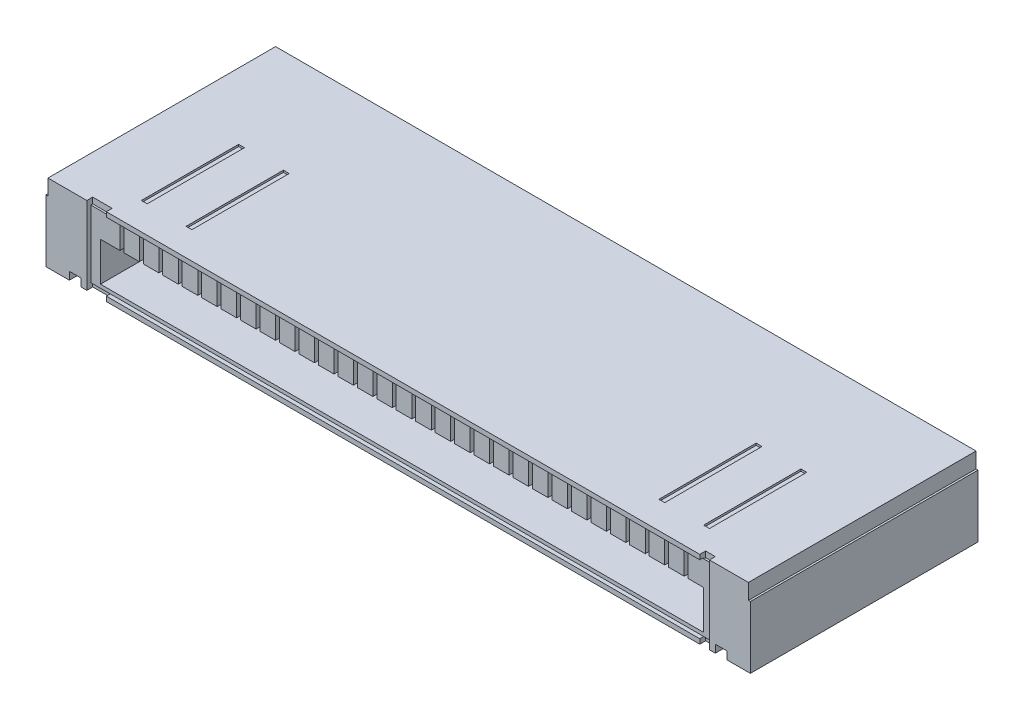
SolidWorks part; units mm, degrees
ref_plane "Plan de face" through (0, 0, 0) normal (0, 0, 1) x (1, 0, 0)
ref_plane "Plan de dessus" through (0, 0, 0) normal (0, 1, 0) x (1, 0, 0)
ref_plane "Plan de droite" through (0, 0, 0) normal (1, 0, 0) x (0, 0, -1)
sketch "Esquisse1" plane through (0, 0, 0) normal (0, 0, 1) x (1, 0, 0)
  line L0 (-42.1545, 0) -> (-21.1545, 0) construction
  line L1 (-42.1545, 2.5) -> (-21.1545, 2.5)
  line L2 (-42.1545, -2.5) -> (-21.1545, -2.5)
  arc A0 (-42.1545, 2.5) -> (-42.1545, -2.5) centre (-42.1545, 0) ccw
  arc A1 (-21.1545, -2.5) -> (-21.1545, 2.5) centre (-21.1545, 0) ccw
  point P3 (-31.6545, 0)
  dimension "D1" = 5
  dimension "D2" = 26
extrude "Boss.-Extru.1" add sketch "Esquisse1" along normal blind 9
sketch "Esquisse3" plane through (0, 0, 9) normal (0, 0, 1) x (1, 0, 0)
  line L0 (-42.1415, 0) -> (-21.1415, 0) construction
  line L1 (-42.1415, 2) -> (-21.1415, 2)
  line L2 (-42.1415, -2) -> (-21.1415, -2)
  arc A0 (-42.1415, 2) -> (-42.1415, -2) centre (-42.1415, 0) ccw
  arc A1 (-21.1415, -2) -> (-21.1415, 2) centre (-21.1415, 0) ccw
  point P3 (-31.6415, 0)
  dimension "D1" = 4
  dimension "D2" = 25
extrude "Enlèv. mat.-Extru.1" cut sketch "Esquisse3" against normal blind 0.15
sketch "Esquisse4" plane through (0, 0, 8.85) normal (0, 0, 1) x (1, 0, 0)
  line L0 (-41.6545, 0.5) -> (-40.6545, 0.5)
  line L1 (-40.6545, 1) -> (-22.6545, 1)
  line L2 (-41.6545, 0.5) -> (-41.6545, -1)
  line L3 (-41.6545, -1) -> (-21.6545, -1)
  line L4 (-21.6545, 0.5) -> (-21.6545, -1)
  line L7 (-40.6545, 0.5) -> (-40.6545, 1)
  line L8 (-22.6545, 1) -> (-22.6545, 0.5)
  line L9 (-22.6545, 0.5) -> (-21.6545, 0.5)
  line L10 (-42.1415, -2) -> (-21.1415, -2) construction
  line L11 (-21.1415, 2) -> (-42.1415, 2) construction
  arc A0 (-42.1545, 2.5) -> (-42.1545, -2.5) centre (-42.1545, 0) ccw construction
  arc A1 (-21.1545, -2.5) -> (-21.1545, 2.5) centre (-21.1545, 0) ccw construction
  point P0 (-31.6545, 0)
  point P11 (-44.6545, 0)
  point P15 (-18.6545, 0)
  dimension "D1" = 3
  dimension "D2" = 3
  dimension "D3" = 1
  dimension "D4" = 1
  dimension "D5" = 1
  dimension "D6" = 0.5
  dimension "D7" = 0.5
  dimension "D8" = 1
extrude "Boss.-Extru.2" add sketch "Esquisse4" along normal blind 6
fillet "Congé1" radius 0.3 1 edges at (-40.6545, 0.5, 11.85)
fillet "Congé2" radius 0.3 1 edges at (-22.6545, 0.5, 11.85)
sketch "Esquisse5" plane through (0, 1, 0) normal (0, 1, 0) x (1, 0, 0)
  line L1 (-22.6545, -8.85) -> (-40.6545, -8.85) construction
  line L2 (-22.6545, -14.85) -> (-40.6545, -14.85) construction
  line L14 (-37.6545, -11.65) -> (-25.6545, -11.65) construction
  line L27 (-31.6545, -8.85) -> (-31.6545, -14.85) construction
  line L28 (-25.5045, -11.65) -> (-25.6545, -11.65)
  line L29 (-25.6545, -11.65) -> (-25.6545, -14.15)
  line L30 (-38.9545, -11.65) -> (-38.8045, -11.65)
  line L31 (-38.9545, -11.65) -> (-38.9545, -14.15)
  line L32 (-38.9545, -14.15) -> (-38.8045, -14.15)
  line L33 (-38.8045, -11.65) -> (-38.8045, -14.15)
  line L34 (-37.8045, -11.65) -> (-37.6545, -11.65)
  line L35 (-37.8045, -11.65) -> (-37.8045, -14.15)
  line L36 (-37.8045, -14.15) -> (-37.6545, -14.15)
  line L37 (-37.6545, -11.65) -> (-37.6545, -14.15)
  line L38 (-25.5045, -14.15) -> (-25.6545, -14.15)
  line L39 (-25.5045, -11.65) -> (-25.5045, -14.15)
  line L40 (-24.3545, -14.15) -> (-24.5045, -14.15)
  line L41 (-24.5045, -11.65) -> (-24.5045, -14.15)
  line L42 (-24.3545, -11.65) -> (-24.3545, -14.15)
  line L43 (-24.3545, -11.65) -> (-24.5045, -11.65)
  point P42 (-31.6545, -11.65)
  dimension "D1" = 0.15
  dimension "D2" = 0.15
  dimension "D3" = 2.5
  dimension "D4" = 1
  dimension "D5" = 1
  dimension "D6" = 12
  dimension "D7" = 2.5
  dimension "D8" = 0.7
extrude "Enlèv. mat.-Extru.2" cut sketch "Esquisse5" against normal blind 0.05
sketch "Esquisse6" plane through (0, 0, 14.85) normal (0, 0, 1) x (1, 0, 0)
  line L1 (-39.6545, 0.8785) -> (-23.6545, 0.8785)
  line L2 (-39.6545, 0.8785) -> (-39.6545, -0.8785)
  line L3 (-39.6545, -0.8785) -> (-23.6545, -0.8785)
  line L4 (-23.6545, 0.8785) -> (-23.6545, -0.8785)
  line L5 (-39.6545, 0.8785) -> (-23.6545, -0.8785) construction
  line L6 (-39.6545, -0.8785) -> (-23.6545, 0.8785) construction
  line L8 (-22.6545, 0.8) -> (-22.6545, 1) construction
  line L9 (-40.6545, 1) -> (-40.6545, 0.8) construction
  point P0 (-31.6545, 0)
  dimension "D1" = 1
  dimension "D2" = 1
extrude "Enlèv. mat.-Extru.3" cut sketch "Esquisse6" against normal blind 0.1
sketch "Esquisse7" plane through (0, 0, 14.75) normal (0, 0, 1) x (1, 0, 0)
  line L0 (-39.6545, 0.8785) -> (-39.6545, -0.8785) construction
  line L1 (-39.4045, 0.2124) -> (-23.9045, 0.2124)
  line L2 (-39.4045, 0.2124) -> (-39.4045, -0.7876)
  line L3 (-39.4045, -0.7876) -> (-23.9045, -0.7876)
  line L4 (-23.9045, 0.2124) -> (-23.9045, -0.7876)
  line L5 (-39.4045, 0.2124) -> (-23.9045, -0.7876) construction
  line L6 (-39.4045, -0.7876) -> (-23.9045, 0.2124) construction
  line L7 (-23.6545, -0.8785) -> (-23.6545, 0.8785) construction
  point P0 (-31.6545, -0.2876)
  dimension "D1" = 0.25
  dimension "D2" = 0.25
  dimension "D3" = 1
extrude "Enlèv. mat.-Extru.4" cut sketch "Esquisse7" against normal blind 4
sketch "Esquisse9" plane through (0, 0, 14.75) normal (0, 0, 1) x (1, 0, 0)
  line L0 (-23.6545, 0.8785) -> (-39.6545, 0.8785) construction
  line L1 (-38.9045, 0.8785) -> (-38.8045, 0.8785)
  line L2 (-38.9045, 0.8785) -> (-38.9045, 0.2124)
  line L3 (-38.9045, 0.2124) -> (-38.8045, 0.2124)
  line L4 (-38.8045, 0.8785) -> (-38.8045, 0.2124)
  line L5 (-23.9045, 0.2124) -> (-39.4045, 0.2124) construction
  line L6 (-39.4045, 0.2124) -> (-39.4045, -0.7876) construction
  line L7 (-38.4045, 0.8785) -> (-38.4045, 0.2124)
  line L8 (-38.4045, 0.8785) -> (-38.3045, 0.8785)
  line L9 (-38.3045, 0.8785) -> (-38.3045, 0.2124)
  line L10 (-38.4045, 0.2124) -> (-38.3045, 0.2124)
  line L11 (-37.9045, 0.8785) -> (-37.9045, 0.2124)
  line L12 (-37.9045, 0.8785) -> (-37.8045, 0.8785)
  line L13 (-37.8045, 0.8785) -> (-37.8045, 0.2124)
  line L14 (-37.9045, 0.2124) -> (-37.8045, 0.2124)
  line L15 (-37.4045, 0.8785) -> (-37.4045, 0.2124)
  line L16 (-37.4045, 0.8785) -> (-37.3045, 0.8785)
  line L17 (-37.3045, 0.8785) -> (-37.3045, 0.2124)
  line L18 (-37.4045, 0.2124) -> (-37.3045, 0.2124)
  line L19 (-36.9045, 0.8785) -> (-36.9045, 0.2124)
  line L20 (-36.9045, 0.8785) -> (-36.8045, 0.8785)
  line L21 (-36.8045, 0.8785) -> (-36.8045, 0.2124)
  line L22 (-36.9045, 0.2124) -> (-36.8045, 0.2124)
  line L23 (-36.4045, 0.8785) -> (-36.4045, 0.2124)
  line L24 (-36.4045, 0.8785) -> (-36.3045, 0.8785)
  line L25 (-36.3045, 0.8785) -> (-36.3045, 0.2124)
  line L26 (-36.4045, 0.2124) -> (-36.3045, 0.2124)
  line L27 (-35.9045, 0.8785) -> (-35.9045, 0.2124)
  line L28 (-35.9045, 0.8785) -> (-35.8045, 0.8785)
  line L29 (-35.8045, 0.8785) -> (-35.8045, 0.2124)
  line L30 (-35.9045, 0.2124) -> (-35.8045, 0.2124)
  line L31 (-35.4045, 0.8785) -> (-35.4045, 0.2124)
  line L32 (-35.4045, 0.8785) -> (-35.3045, 0.8785)
  line L33 (-35.3045, 0.8785) -> (-35.3045, 0.2124)
  line L34 (-35.4045, 0.2124) -> (-35.3045, 0.2124)
  line L35 (-34.9045, 0.8785) -> (-34.9045, 0.2124)
  line L36 (-34.9045, 0.8785) -> (-34.8045, 0.8785)
  line L37 (-34.8045, 0.8785) -> (-34.8045, 0.2124)
  line L38 (-34.9045, 0.2124) -> (-34.8045, 0.2124)
  line L39 (-34.4045, 0.8785) -> (-34.4045, 0.2124)
  line L40 (-34.4045, 0.8785) -> (-34.3045, 0.8785)
  line L41 (-34.3045, 0.8785) -> (-34.3045, 0.2124)
  line L42 (-34.4045, 0.2124) -> (-34.3045, 0.2124)
  line L43 (-33.9045, 0.8785) -> (-33.9045, 0.2124)
  line L44 (-33.9045, 0.8785) -> (-33.8045, 0.8785)
  line L45 (-33.8045, 0.8785) -> (-33.8045, 0.2124)
  line L46 (-33.9045, 0.2124) -> (-33.8045, 0.2124)
  line L47 (-33.4045, 0.8785) -> (-33.4045, 0.2124)
  line L48 (-33.4045, 0.8785) -> (-33.3045, 0.8785)
  line L49 (-33.3045, 0.8785) -> (-33.3045, 0.2124)
  line L50 (-33.4045, 0.2124) -> (-33.3045, 0.2124)
  line L51 (-32.9045, 0.8785) -> (-32.9045, 0.2124)
  line L52 (-32.9045, 0.8785) -> (-32.8045, 0.8785)
  line L53 (-32.8045, 0.8785) -> (-32.8045, 0.2124)
  line L54 (-32.9045, 0.2124) -> (-32.8045, 0.2124)
  line L55 (-32.4045, 0.8785) -> (-32.4045, 0.2124)
  line L56 (-32.4045, 0.8785) -> (-32.3045, 0.8785)
  line L57 (-32.3045, 0.8785) -> (-32.3045, 0.2124)
  line L58 (-32.4045, 0.2124) -> (-32.3045, 0.2124)
  line L59 (-31.9045, 0.8785) -> (-31.9045, 0.2124)
  line L60 (-31.9045, 0.8785) -> (-31.8045, 0.8785)
  line L61 (-31.8045, 0.8785) -> (-31.8045, 0.2124)
  line L62 (-31.9045, 0.2124) -> (-31.8045, 0.2124)
  line L63 (-31.4045, 0.8785) -> (-31.4045, 0.2124)
  line L64 (-31.4045, 0.8785) -> (-31.3045, 0.8785)
  line L65 (-31.3045, 0.8785) -> (-31.3045, 0.2124)
  line L66 (-31.4045, 0.2124) -> (-31.3045, 0.2124)
  line L67 (-30.9045, 0.8785) -> (-30.9045, 0.2124)
  line L68 (-30.9045, 0.8785) -> (-30.8045, 0.8785)
  line L69 (-30.8045, 0.8785) -> (-30.8045, 0.2124)
  line L70 (-30.9045, 0.2124) -> (-30.8045, 0.2124)
  line L71 (-30.4045, 0.8785) -> (-30.4045, 0.2124)
  line L72 (-30.4045, 0.8785) -> (-30.3045, 0.8785)
  line L73 (-30.3045, 0.8785) -> (-30.3045, 0.2124)
  line L74 (-30.4045, 0.2124) -> (-30.3045, 0.2124)
  line L75 (-29.9045, 0.8785) -> (-29.9045, 0.2124)
  line L76 (-29.9045, 0.8785) -> (-29.8045, 0.8785)
  line L77 (-29.8045, 0.8785) -> (-29.8045, 0.2124)
  line L78 (-29.9045, 0.2124) -> (-29.8045, 0.2124)
  line L79 (-29.4045, 0.8785) -> (-29.4045, 0.2124)
  line L80 (-29.4045, 0.8785) -> (-29.3045, 0.8785)
  line L81 (-29.3045, 0.8785) -> (-29.3045, 0.2124)
  line L82 (-29.4045, 0.2124) -> (-29.3045, 0.2124)
  line L83 (-28.9045, 0.8785) -> (-28.9045, 0.2124)
  line L84 (-28.9045, 0.8785) -> (-28.8045, 0.8785)
  line L85 (-28.8045, 0.8785) -> (-28.8045, 0.2124)
  line L86 (-28.9045, 0.2124) -> (-28.8045, 0.2124)
  line L87 (-28.4045, 0.8785) -> (-28.4045, 0.2124)
  line L88 (-28.4045, 0.8785) -> (-28.3045, 0.8785)
  line L89 (-28.3045, 0.8785) -> (-28.3045, 0.2124)
  line L90 (-28.4045, 0.2124) -> (-28.3045, 0.2124)
  line L91 (-27.9045, 0.8785) -> (-27.9045, 0.2124)
  line L92 (-27.9045, 0.8785) -> (-27.8045, 0.8785)
  line L93 (-27.8045, 0.8785) -> (-27.8045, 0.2124)
  line L94 (-27.9045, 0.2124) -> (-27.8045, 0.2124)
  line L95 (-27.4045, 0.8785) -> (-27.4045, 0.2124)
  line L96 (-27.4045, 0.8785) -> (-27.3045, 0.8785)
  line L97 (-27.3045, 0.8785) -> (-27.3045, 0.2124)
  line L98 (-27.4045, 0.2124) -> (-27.3045, 0.2124)
  line L99 (-26.9045, 0.8785) -> (-26.9045, 0.2124)
  line L100 (-26.9045, 0.8785) -> (-26.8045, 0.8785)
  line L101 (-26.8045, 0.8785) -> (-26.8045, 0.2124)
  line L102 (-26.9045, 0.2124) -> (-26.8045, 0.2124)
  line L103 (-26.4045, 0.8785) -> (-26.4045, 0.2124)
  line L104 (-26.4045, 0.8785) -> (-26.3045, 0.8785)
  line L105 (-26.3045, 0.8785) -> (-26.3045, 0.2124)
  line L106 (-26.4045, 0.2124) -> (-26.3045, 0.2124)
  line L107 (-25.9045, 0.8785) -> (-25.9045, 0.2124)
  line L108 (-25.9045, 0.8785) -> (-25.8045, 0.8785)
  line L109 (-25.8045, 0.8785) -> (-25.8045, 0.2124)
  line L110 (-25.9045, 0.2124) -> (-25.8045, 0.2124)
  line L111 (-25.4045, 0.8785) -> (-25.4045, 0.2124)
  line L112 (-25.4045, 0.8785) -> (-25.3045, 0.8785)
  line L113 (-25.3045, 0.8785) -> (-25.3045, 0.2124)
  line L114 (-25.4045, 0.2124) -> (-25.3045, 0.2124)
  line L115 (-24.9045, 0.8785) -> (-24.9045, 0.2124)
  line L116 (-24.9045, 0.8785) -> (-24.8045, 0.8785)
  line L117 (-24.8045, 0.8785) -> (-24.8045, 0.2124)
  line L118 (-24.9045, 0.2124) -> (-24.8045, 0.2124)
  line L119 (-24.4045, 0.8785) -> (-24.4045, 0.2124)
  line L120 (-24.4045, 0.8785) -> (-24.3045, 0.8785)
  line L121 (-24.3045, 0.8785) -> (-24.3045, 0.2124)
  line L122 (-24.4045, 0.2124) -> (-24.3045, 0.2124)
  line L123 (-38.9045, 0.8785) -> (-38.4045, 0.8785) construction
  dimension "D1" = 0.5
  dimension "D2" = 0.1
  dimension "D4" = 0.5
  dimension "D3" = 30
extrude "Enlèv. mat.-Extru.5" cut sketch "Esquisse9" against normal blind 0.1
sketch "Esquisse10" plane through (0, 0.2124, 0) normal (0, -1, 0) x (1, 0, 0)
  line L0 (-23.9045, 10.75) -> (-39.4045, 10.75) construction
  line L1 (-38.9045, 14.65) -> (-38.8045, 14.65)
  line L2 (-38.9045, 14.65) -> (-38.9045, 10.75)
  line L3 (-38.9045, 10.75) -> (-38.8045, 10.75)
  line L4 (-38.8045, 14.65) -> (-38.8045, 10.75)
  line L5 (-38.4045, 14.65) -> (-38.3045, 14.65)
  line L6 (-38.4045, 14.65) -> (-38.4045, 10.75)
  line L7 (-38.3045, 14.65) -> (-38.3045, 10.75)
  line L8 (-37.9045, 14.65) -> (-37.8045, 14.65)
  line L9 (-37.9045, 14.65) -> (-37.9045, 10.75)
  line L10 (-37.8045, 14.65) -> (-37.8045, 10.75)
  line L11 (-37.4045, 14.65) -> (-37.3045, 14.65)
  line L12 (-37.4045, 14.65) -> (-37.4045, 10.75)
  line L13 (-37.3045, 14.65) -> (-37.3045, 10.75)
  line L14 (-36.9045, 14.65) -> (-36.8045, 14.65)
  line L15 (-36.9045, 14.65) -> (-36.9045, 10.75)
  line L16 (-36.8045, 14.65) -> (-36.8045, 10.75)
  line L17 (-36.4045, 14.65) -> (-36.3045, 14.65)
  line L18 (-36.4045, 14.65) -> (-36.4045, 10.75)
  line L19 (-36.3045, 14.65) -> (-36.3045, 10.75)
  line L20 (-35.9045, 14.65) -> (-35.8045, 14.65)
  line L21 (-35.9045, 14.65) -> (-35.9045, 10.75)
  line L22 (-35.8045, 14.65) -> (-35.8045, 10.75)
  line L23 (-35.4045, 14.65) -> (-35.3045, 14.65)
  line L24 (-35.4045, 14.65) -> (-35.4045, 10.75)
  line L25 (-35.3045, 14.65) -> (-35.3045, 10.75)
  line L26 (-34.9045, 14.65) -> (-34.8045, 14.65)
  line L27 (-34.9045, 14.65) -> (-34.9045, 10.75)
  line L28 (-34.8045, 14.65) -> (-34.8045, 10.75)
  line L29 (-34.4045, 14.65) -> (-34.3045, 14.65)
  line L30 (-34.4045, 14.65) -> (-34.4045, 10.75)
  line L31 (-34.3045, 14.65) -> (-34.3045, 10.75)
  line L32 (-33.9045, 14.65) -> (-33.8045, 14.65)
  line L33 (-33.9045, 14.65) -> (-33.9045, 10.75)
  line L34 (-33.8045, 14.65) -> (-33.8045, 10.75)
  line L35 (-33.4045, 14.65) -> (-33.3045, 14.65)
  line L36 (-33.4045, 14.65) -> (-33.4045, 10.75)
  line L37 (-33.3045, 14.65) -> (-33.3045, 10.75)
  line L38 (-32.9045, 14.65) -> (-32.8045, 14.65)
  line L39 (-32.9045, 14.65) -> (-32.9045, 10.75)
  line L40 (-32.8045, 14.65) -> (-32.8045, 10.75)
  line L41 (-32.4045, 14.65) -> (-32.3045, 14.65)
  line L42 (-32.4045, 14.65) -> (-32.4045, 10.75)
  line L43 (-32.3045, 14.65) -> (-32.3045, 10.75)
  line L44 (-31.9045, 14.65) -> (-31.8045, 14.65)
  line L45 (-31.9045, 14.65) -> (-31.9045, 10.75)
  line L46 (-31.8045, 14.65) -> (-31.8045, 10.75)
  line L47 (-31.4045, 14.65) -> (-31.3045, 14.65)
  line L48 (-31.4045, 14.65) -> (-31.4045, 10.75)
  line L49 (-31.3045, 14.65) -> (-31.3045, 10.75)
  line L50 (-30.9045, 14.65) -> (-30.8045, 14.65)
  line L51 (-30.9045, 14.65) -> (-30.9045, 10.75)
  line L52 (-30.8045, 14.65) -> (-30.8045, 10.75)
  line L53 (-30.4045, 14.65) -> (-30.3045, 14.65)
  line L54 (-30.4045, 14.65) -> (-30.4045, 10.75)
  line L55 (-30.3045, 14.65) -> (-30.3045, 10.75)
  line L56 (-29.9045, 14.65) -> (-29.8045, 14.65)
  line L57 (-29.9045, 14.65) -> (-29.9045, 10.75)
  line L58 (-29.8045, 14.65) -> (-29.8045, 10.75)
  line L59 (-29.4045, 14.65) -> (-29.3045, 14.65)
  line L60 (-29.4045, 14.65) -> (-29.4045, 10.75)
  line L61 (-29.3045, 14.65) -> (-29.3045, 10.75)
  line L62 (-28.9045, 14.65) -> (-28.8045, 14.65)
  line L63 (-28.9045, 14.65) -> (-28.9045, 10.75)
  line L64 (-28.8045, 14.65) -> (-28.8045, 10.75)
  line L65 (-28.4045, 14.65) -> (-28.3045, 14.65)
  line L66 (-28.4045, 14.65) -> (-28.4045, 10.75)
  line L67 (-28.3045, 14.65) -> (-28.3045, 10.75)
  line L68 (-27.9045, 14.65) -> (-27.8045, 14.65)
  line L69 (-27.9045, 14.65) -> (-27.9045, 10.75)
  line L70 (-27.8045, 14.65) -> (-27.8045, 10.75)
  line L71 (-27.4045, 14.65) -> (-27.3045, 14.65)
  line L72 (-27.4045, 14.65) -> (-27.4045, 10.75)
  line L73 (-27.3045, 14.65) -> (-27.3045, 10.75)
  line L74 (-26.9045, 14.65) -> (-26.8045, 14.65)
  line L75 (-26.9045, 14.65) -> (-26.9045, 10.75)
  line L76 (-26.8045, 14.65) -> (-26.8045, 10.75)
  line L77 (-26.4045, 14.65) -> (-26.3045, 14.65)
  line L78 (-26.4045, 14.65) -> (-26.4045, 10.75)
  line L79 (-26.3045, 14.65) -> (-26.3045, 10.75)
  line L80 (-25.9045, 14.65) -> (-25.8045, 14.65)
  line L81 (-25.9045, 14.65) -> (-25.9045, 10.75)
  line L82 (-25.8045, 14.65) -> (-25.8045, 10.75)
  line L83 (-25.4045, 14.65) -> (-25.3045, 14.65)
  line L84 (-25.4045, 14.65) -> (-25.4045, 10.75)
  line L85 (-25.3045, 14.65) -> (-25.3045, 10.75)
  line L86 (-24.9045, 14.65) -> (-24.8045, 14.65)
  line L87 (-24.9045, 14.65) -> (-24.9045, 10.75)
  line L88 (-24.8045, 14.65) -> (-24.8045, 10.75)
  line L89 (-24.4045, 14.65) -> (-24.3045, 14.65)
  line L90 (-24.4045, 14.65) -> (-24.4045, 10.75)
  line L91 (-24.3045, 14.65) -> (-24.3045, 10.75)
  line L92 (-38.9045, 14.65) -> (-38.4045, 14.65) construction
  line L93 (-38.4045, 10.75) -> (-38.3045, 10.75)
  line L94 (-37.9045, 10.75) -> (-37.8045, 10.75)
  line L95 (-37.4045, 10.75) -> (-37.3045, 10.75)
  line L96 (-36.9045, 10.75) -> (-36.8045, 10.75)
  line L97 (-36.4045, 10.75) -> (-36.3045, 10.75)
  line L98 (-35.9045, 10.75) -> (-35.8045, 10.75)
  line L99 (-35.4045, 10.75) -> (-35.3045, 10.75)
  line L100 (-34.9045, 10.75) -> (-34.8045, 10.75)
  line L101 (-34.4045, 10.75) -> (-34.3045, 10.75)
  line L102 (-33.9045, 10.75) -> (-33.8045, 10.75)
  line L103 (-33.4045, 10.75) -> (-33.3045, 10.75)
  line L104 (-32.9045, 10.75) -> (-32.8045, 10.75)
  line L105 (-32.4045, 10.75) -> (-32.3045, 10.75)
  line L106 (-31.9045, 10.75) -> (-31.8045, 10.75)
  line L107 (-31.4045, 10.75) -> (-31.3045, 10.75)
  line L108 (-30.9045, 10.75) -> (-30.8045, 10.75)
  line L109 (-30.4045, 10.75) -> (-30.3045, 10.75)
  line L110 (-29.9045, 10.75) -> (-29.8045, 10.75)
  line L111 (-29.4045, 10.75) -> (-29.3045, 10.75)
  line L112 (-28.9045, 10.75) -> (-28.8045, 10.75)
  line L113 (-28.4045, 10.75) -> (-28.3045, 10.75)
  line L114 (-27.9045, 10.75) -> (-27.8045, 10.75)
  line L115 (-27.4045, 10.75) -> (-27.3045, 10.75)
  line L116 (-26.9045, 10.75) -> (-26.8045, 10.75)
  line L117 (-26.4045, 10.75) -> (-26.3045, 10.75)
  line L118 (-25.9045, 10.75) -> (-25.8045, 10.75)
  line L119 (-25.4045, 10.75) -> (-25.3045, 10.75)
  line L120 (-24.9045, 10.75) -> (-24.8045, 10.75)
  line L121 (-24.4045, 10.75) -> (-24.3045, 10.75)
  dimension "D2" = 0.5
  dimension "D1" = 30
extrude "Enlèv. mat.-Extru.6" cut sketch "Esquisse10" against normal blind 0.1
sketch "Esquisse11" plane through (-21.6545, 0, 0) normal (1, 0, 0) x (0, 0, -1)
  line L1 (-14.85, 0.25) -> (-8.85, 0.25)
  line L2 (-14.85, 0.25) -> (-14.85, -0.25)
  line L3 (-14.85, -0.25) -> (-8.85, -0.25)
  line L4 (-8.85, 0.25) -> (-8.85, -0.25)
  line L5 (-14.85, 0.25) -> (-8.85, -0.25) construction
  line L6 (-14.85, -0.25) -> (-8.85, 0.25) construction
  line L7 (-14.85, -1) -> (-14.85, 0.5) construction
  line L8 (-8.85, -1) -> (-8.85, 0.5) construction
  point P0 (-11.85, 0)
  dimension "D1" = 0.5
extrude "Boss.-Extru.3" [suppressed] add sketch "Esquisse11" along normal blind 1
sketch "Esquisse13" [suppressed] plane through (0, -0.25, 0) normal (0, -1, 0) x (1, 0, 0)
  line L2 (-20.6545, 14.85) -> (-20.6545, 8.85) construction
  line L3 (-20.6545, 12.8999) -> (-21.6545, 11.9855)
  line L4 (-21.6545, 14.85) -> (-21.6545, 8.85) construction
  line L6 (-21.6545, 11.9855) -> (-21.6545, 8.85)
  line L7 (-21.6545, 8.85) -> (-20.6545, 8.85)
  line L8 (-20.6545, 8.85) -> (-20.6545, 12.8999)
extrude "Enlèv. mat.-Extru.7" [suppressed] cut sketch "Esquisse13" against normal blind 1
sketch "Esquisse14" [suppressed] plane through (0, -0.25, 0) normal (0, -1, 0) x (1, 0, 0)
  line L0 (-20.6545, 12.8999) -> (-21.6545, 14.5107)
  line L1 (-21.6545, 14.85) -> (-21.6545, 11.9855) construction
  line L2 (-21.6545, 14.5107) -> (-21.6545, 14.85)
  line L3 (-21.6545, 14.85) -> (-20.6545, 14.85)
  line L4 (-20.6545, 14.85) -> (-20.6545, 12.8999)
extrude "Enlèv. mat.-Extru.8" [suppressed] cut sketch "Esquisse14" against normal blind 1
sketch "Esquisse15" [suppressed] plane through (-21.6545, 0, 0) normal (1, 0, 0) x (0, 0, -1)
  line L0 (-8.85, -1) -> (-8.85, 0.5) construction
  line L1 (-11.9855, 0.25) -> (-8.85, 0.25)
  line L2 (-11.9855, 0.25) -> (-11.9855, -0.25)
  line L3 (-11.9855, -0.25) -> (-8.85, -0.25)
  line L4 (-8.85, 0.25) -> (-8.85, -0.25)
  line L5 (-14.85, -1) -> (-14.85, 0.5) construction
  line L6 (-14.5107, 0.25) -> (-14.85, 0.25)
  line L7 (-14.5107, 0.25) -> (-14.5107, -0.25)
  line L8 (-14.5107, -0.25) -> (-14.85, -0.25)
  line L9 (-14.85, 0.25) -> (-14.85, -0.25)
extrude "Enlèv. mat.-Extru.9" [suppressed] cut sketch "Esquisse15" against normal blind 0.05
fillet "Congé3" [suppressed] radius 0.05
sketch "Esquisse16" plane through (-41.6545, 0, 0) normal (-1, 0, 0) x (0, 0, 1)
  line L0 (14.85, 0.5) -> (14.85, -1) construction
  line L1 (14.85, 0.2491) -> (8.85, 0.2491)
  line L2 (14.85, 0.2491) -> (14.85, -0.2509)
  line L3 (14.85, -0.2509) -> (8.85, -0.2509)
  line L4 (8.85, 0.2491) -> (8.85, -0.2509)
  line L5 (8.85, 0.5) -> (8.85, -1) construction
  dimension "D1" = 0.5
extrude "Boss.-Extru.4" [suppressed] add sketch "Esquisse16" along normal blind 1
sketch "Esquisse17" [suppressed] plane through (0, 0.2491, 0) normal (0, 1, 0) x (1, 0, 0)
  line L0 (-42.6545, -8.85) -> (-41.6545, -8.85)
  line L1 (-41.6545, -8.85) -> (-41.6545, -11.9856)
  line L2 (-41.6545, -14.85) -> (-41.6545, -8.85) construction
  line L3 (-41.6545, -11.9856) -> (-42.6545, -12.9)
  line L4 (-42.6545, -14.85) -> (-42.6545, -8.85) construction
  line L5 (-42.6545, -12.9) -> (-42.6545, -8.85)
  dimension "D1" = 1.95
  dimension "D2" = 132.44
extrude "Enlèv. mat.-Extru.10" [suppressed] cut sketch "Esquisse17" against normal blind 1
sketch "Esquisse18" [suppressed] plane through (0, 0.2491, 0) normal (0, 1, 0) x (1, 0, 0)
  line L0 (-42.6545, -12.9) -> (-41.6545, -14.511)
  line L1 (-41.6545, -14.85) -> (-41.6545, -11.9856) construction
  line L2 (-42.6545, -12.9) -> (-42.6545, -14.85)
  line L3 (-42.6545, -14.85) -> (-41.6545, -14.85)
  line L4 (-41.6545, -14.85) -> (-41.6545, -14.511)
  dimension "D1" = 0.339
extrude "Enlèv. mat.-Extru.11" [suppressed] cut sketch "Esquisse18" against normal blind 1
sketch "Esquisse19" [suppressed] plane through (-41.6545, 0, 0) normal (-1, 0, 0) x (0, 0, 1)
  line L0 (8.85, 0.5) -> (8.85, -1) construction
  line L1 (11.9856, 0.2491) -> (8.85, 0.2491)
  line L2 (11.9856, 0.2491) -> (11.9856, -0.25)
  line L3 (11.9856, -0.25) -> (8.85, -0.25)
  line L4 (8.85, 0.2491) -> (8.85, -0.25)
  line L5 (14.85, 0.5) -> (14.85, -1) construction
  line L6 (14.511, 0.2491) -> (14.85, 0.2491)
  line L7 (14.511, 0.2491) -> (14.511, -0.25)
  line L8 (14.511, -0.25) -> (14.85, -0.25)
  line L9 (14.85, 0.2491) -> (14.85, -0.25)
extrude "Enlèv. mat.-Extru.12" [suppressed] cut sketch "Esquisse19" against normal blind 0.05
fillet "Congé4" [suppressed] radius 0.05
sketch "Esquisse20" plane through (0, 1, 0) normal (0, 1, 0) x (1, 0, 0)
  line L0 (-22.6545, -14.85) -> (-40.6545, -14.85) construction
  line L1 (-39.6545, -14.85) -> (-39.1545, -14.85)
  line L2 (-39.6545, -14.85) -> (-39.6545, -14.7)
  line L3 (-39.6545, -14.7) -> (-39.1545, -14.7)
  line L4 (-39.1545, -14.85) -> (-39.1545, -14.7)
  line L7 (-23.9045, -14.85) -> (-23.6545, -14.85)
  line L8 (-23.9045, -14.85) -> (-23.9045, -14.7)
  line L9 (-23.9045, -14.7) -> (-23.6545, -14.7)
  line L10 (-23.6545, -14.85) -> (-23.6545, -14.7)
  line L11 (-39.6545, -14.75) -> (-39.6545, -14.85) construction
  line L12 (-23.6545, -14.75) -> (-23.6545, -14.85) construction
  dimension "D1" = 0.15
  dimension "D2" = 0.5
  dimension "D3" = 0.15
  dimension "D4" = 0.25
extrude "Enlèv. mat.-Extru.13" cut sketch "Esquisse20" against normal blind 0.15
sketch "Esquisse21" plane through (0, -1, 0) normal (0, -1, 0) x (1, 0, 0)
  line L1 (-37.6545, 14.15) -> (-25.6545, 14.15) construction
  line L2 (-31.6545, 14.85) -> (-31.6545, 8.85) construction
  line L3 (-25.5045, 14.15) -> (-25.6545, 14.15)
  line L4 (-25.6545, 14.15) -> (-25.6545, 11.65)
  line L5 (-41.6545, 14.85) -> (-21.6545, 14.85) construction
  line L6 (-38.9545, 14.15) -> (-38.8045, 14.15)
  line L7 (-38.9545, 14.15) -> (-38.9545, 11.65)
  line L8 (-38.9545, 11.65) -> (-38.8045, 11.65)
  line L9 (-38.8045, 14.15) -> (-38.8045, 11.65)
  line L10 (-37.8045, 14.15) -> (-37.6545, 14.15)
  line L11 (-37.8045, 14.15) -> (-37.8045, 11.65)
  line L12 (-37.8045, 11.65) -> (-37.6545, 11.65)
  line L13 (-37.6545, 14.15) -> (-37.6545, 11.65)
  line L14 (-41.6545, 8.85) -> (-21.6545, 8.85) construction
  line L15 (-25.5045, 11.65) -> (-25.6545, 11.65)
  line L16 (-25.5045, 14.15) -> (-25.5045, 11.65)
  line L17 (-24.3545, 11.65) -> (-24.5045, 11.65)
  line L18 (-24.5045, 14.15) -> (-24.5045, 11.65)
  line L19 (-24.3545, 14.15) -> (-24.3545, 11.65)
  line L20 (-24.3545, 14.15) -> (-24.5045, 14.15)
  point P23 (-31.6545, 14.15)
  dimension "D2" = 12
  dimension "D3" = 0.7
  dimension "D4" = 1
  dimension "D5" = 2.5
  dimension "D6" = 0.15
  dimension "D7" = 2.5
  dimension "D8" = 0.15
  dimension "D10" = 1
extrude "Enlèv. mat.-Extru.14" cut sketch "Esquisse21" against normal blind 0.05
sketch "Esquisse22" plane through (0, -1, 0) normal (0, -1, 0) x (1, 0, 0)
  line L0 (-41.6545, 14.85) -> (-21.6545, 14.85) construction
  line L1 (-40.1045, 14.85) -> (-39.8045, 14.85)
  line L2 (-40.1045, 14.85) -> (-40.1045, 11.85)
  line L3 (-40.1045, 11.85) -> (-39.8045, 11.85)
  line L4 (-39.8045, 14.85) -> (-39.8045, 11.85)
  line L6 (-23.2045, 14.85) -> (-23.5045, 14.85)
  line L7 (-23.5045, 14.85) -> (-23.5045, 11.85)
  line L8 (-23.2045, 11.85) -> (-23.5045, 11.85)
  line L9 (-23.2045, 14.85) -> (-23.2045, 11.85)
  dimension "D1" = 0.3
  dimension "D2" = 0.4
  dimension "D3" = 0.4
  dimension "D4" = 3
extrude "Enlèv. mat.-Extru.15" cut sketch "Esquisse22" against normal blind 0.2
sketch "Sketch1" plane through (0, 0, 0) normal (0, 0, 1) x (1, 0, 0)
  line L1 (-45.9289, 2.7786) -> (-17.5113, 2.7786)
  line L2 (-45.9289, 2.7786) -> (-45.9289, -3.4334)
  line L3 (-45.9289, -3.4334) -> (-17.5113, -3.4334)
  line L4 (-17.5113, 2.7786) -> (-17.5113, -3.4334)
extrude "Cut-Extrude1" cut sketch "Sketch1" along normal blind 9
sketch "Sketch2" plane through (0, -1, 0) normal (0, -1, 0) x (1, 0, 0)
  line L0 (-39.6545, 14.7) -> (-39.1545, 14.7)
  line L1 (-39.6545, 14.7) -> (-39.6545, 14.85)
  line L2 (-39.6545, 14.85) -> (-39.1545, 14.85)
  line L3 (-39.1545, 14.7) -> (-39.1545, 14.85)
  line L4 (-23.9045, 14.7) -> (-23.6545, 14.7)
  line L5 (-23.9045, 14.7) -> (-23.9045, 14.85)
  line L6 (-23.9045, 14.85) -> (-23.6545, 14.85)
  line L7 (-23.6545, 14.7) -> (-23.6545, 14.85)
  line L8 (-39.8045, 14.85) -> (-23.5045, 14.85) construction
  dimension "D1" = 0.5
  dimension "D2" = 0.15
  dimension "D3" = 0.25
  dimension "D4" = 0.15
extrude "Cut-Extrude2" cut sketch "Sketch2" against normal up to vertex (0.1215 mm away) up to point (-39.6545, -0.8785, 14.85)
sketch "Sketch3" plane through (0, 0, 9) normal (0, 0, -1) x (-1, 0, 0)
  line L0 (41.6545, -1) -> (21.6545, -1) construction
  line L1 (40.7045, 0.6) -> (22.6045, 0.6) construction
  line L2 (31.6545, 0.6) -> (31.6545, -1) construction
  line L3 (40.7045, -1) -> (22.6045, -1) construction
  line L4 (22.6045, 0.6) -> (22.6045, -1)
  line L6 (21.6545, -1) -> (21.6545, 0.5) construction
  line L7 (22.6045, 0.6) -> (22.6545, 0.6)
  line L8 (22.6545, 0.6) -> (22.6545, 1)
  line L9 (22.6545, 1) -> (21.6545, 1)
  line L10 (21.6545, 1) -> (21.6545, -1)
  line L11 (21.6545, -1) -> (22.6045, -1)
  line L12 (41.6545, -1) -> (40.7045, -1)
  line L13 (41.6545, 1) -> (41.6545, -1)
  line L14 (40.6545, 1) -> (41.6545, 1)
  line L15 (40.6545, 0.6) -> (40.6545, 1)
  line L16 (40.7045, 0.6) -> (40.6545, 0.6)
  line L17 (40.7045, 0.6) -> (40.7045, -1)
  dimension "D1" = 0.95
  dimension "D2" = 1.6
  dimension "D3" = 0.95
extrude "Cut-Extrude5" cut sketch "Sketch3" against normal through all
